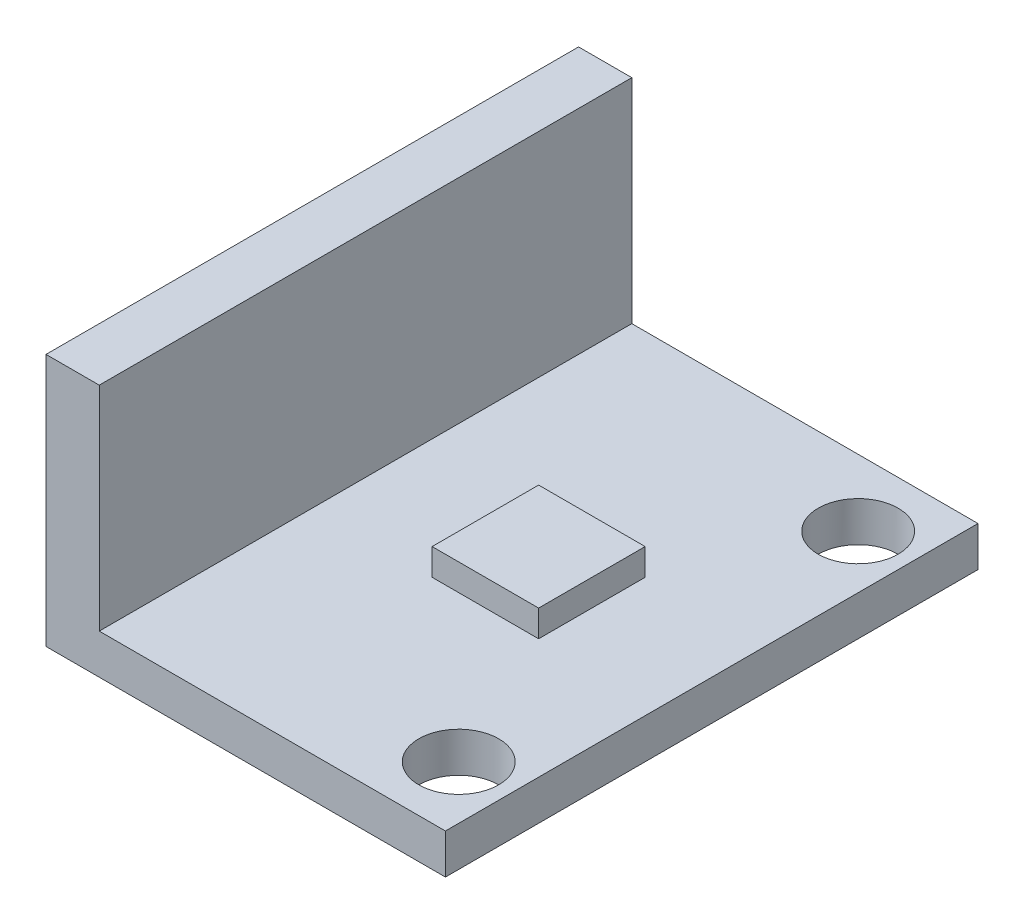
SolidWorks part; units mm, degrees
ref_plane "Plan de face" through (0, 0, 0) normal (0, 0, 1) x (1, 0, 0)
ref_plane "Plan de dessus" through (0, 0, 0) normal (0, 1, 0) x (1, 0, 0)
ref_plane "Plan de droite" through (0, 0, 0) normal (1, 0, 0) x (0, 0, -1)
sketch "Esquisse1" plane through (0, 0, 0) normal (0, 1, 0) x (1, 0, 0)
  line L1 (-7.5, -10) -> (7.5, -10)
  line L2 (-7.5, -10) -> (-7.5, 10)
  line L3 (-7.5, 10) -> (7.5, 10)
  line L4 (7.5, -10) -> (7.5, 10)
  line L5 (-7.5, -10) -> (7.5, 10) construction
  line L6 (-7.5, 10) -> (7.5, -10) construction
  point P0 (0, 0)
  dimension "D1" = 20
  dimension "D2" = 15
extrude "Boss.-Extru.1" add sketch "Esquisse1" along normal blind 1.5
sketch "Esquisse2" plane through (0, 1.5, 0) normal (0, 1, 0) x (1, 0, 0)
  line L1 (7.5, -10) -> (7.5, 10) construction
  line L2 (7.5, 10) -> (-7.5, 10) construction
  circle A0 centre (5.5, 7.5) radius 1.5
  point P4 (0, 0)
  dimension "D3" = 3
  dimension "D1" = 2
  dimension "D2" = 2.5
extrude "Enlèv. mat.-Extru.1" cut sketch "Esquisse2" against normal up to next
mirror "Symétrie1" about plane through (0, 0, 0) normal (0, 0, 1) of "Enlèv. mat.-Extru.1"
sketch "Esquisse3" plane through (0, 1.5, 0) normal (0, 1, 0) x (1, 0, 0)
  line L0 (-7.5, 10) -> (-7.5, -10) construction
  line L1 (-7.5, 10) -> (-5.5, 10)
  line L2 (-7.5, 10) -> (-7.5, -10)
  line L3 (-7.5, -10) -> (-5.5, -10)
  line L4 (-5.5, 10) -> (-5.5, -10)
  point P6 (-5.5, 0)
  dimension "D1" = 2
  dimension "D2" = 20
extrude "Boss.-Extru.2" add sketch "Esquisse3" along normal blind 8 contours L4 L3 L2 L1
sketch "Esquisse4" plane through (0, 1.5, 0) normal (0, 1, 0) x (1, 0, 0)
  line L0 (7.5, -10) -> (7.5, 10) construction
  line L1 (-1, 2) -> (3, 2)
  line L2 (-1, 2) -> (-1, -2)
  line L3 (-1, -2) -> (3, -2)
  line L4 (3, 2) -> (3, -2)
  point P4 (-1, 0)
  dimension "D1" = 4
  dimension "D2" = 4.5
extrude "Boss.-Extru.3" add sketch "Esquisse4" along normal blind 1
